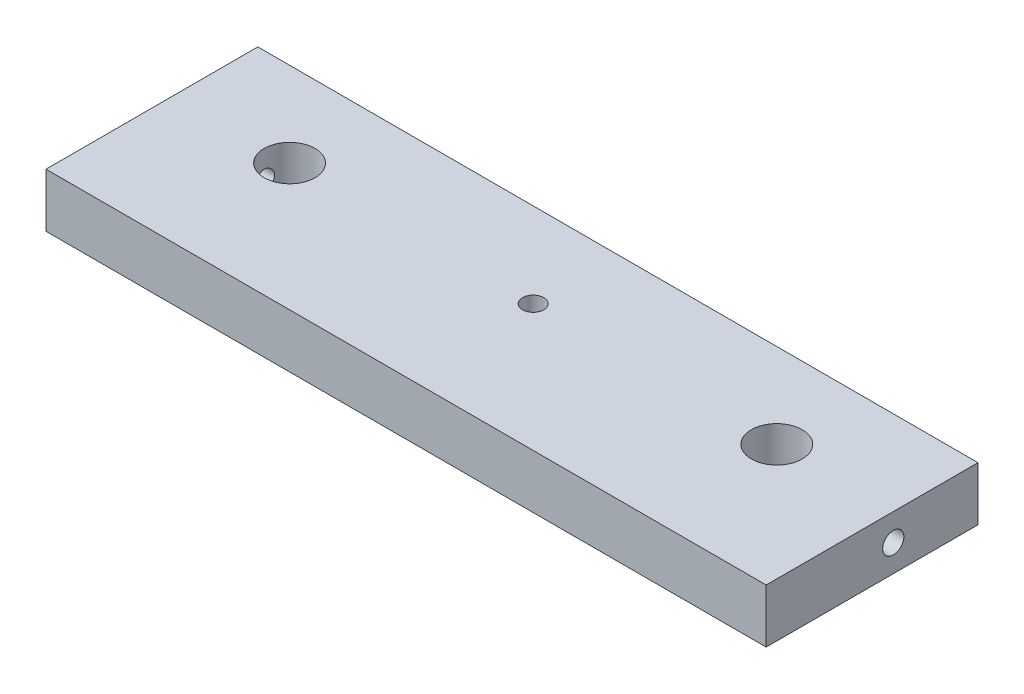
SolidWorks part; units mm, degrees
material "Liga 1060"
ref_plane "Frontal" through (0, 0, 0) normal (0, 0, 1) x (1, 0, 0)
ref_plane "Superior" through (0, 0, 0) normal (0, 1, 0) x (1, 0, 0)
ref_plane "Direito" through (0, 0, 0) normal (1, 0, 0) x (0, 0, -1)
sketch "Esboço1" plane through (0, 0, 0) normal (0, 1, 0) x (1, 0, 0)
  line L1 (-75, 20) -> (75, 20)
  line L2 (-75, 20) -> (-75, -20)
  line L3 (-75, -20) -> (75, -20)
  line L4 (75, 20) -> (75, -20)
  line L5 (-75, 20) -> (75, -20) construction
  line L6 (-75, -20) -> (75, 20) construction
  circle A0 centre (0, 0) radius 2.5
  circle A1 centre (-57.5, 0) radius 6
  circle A2 centre (57.5, 0) radius 6
  point P0 (0, 0)
  dimension "D3" = 5
  dimension "D4" = 12
  dimension "D5" = 12
  dimension "D1" = 150
  dimension "D2" = 40
  dimension "D6" = 17.5
  dimension "D7" = 17.5
  dimension "D8" = 20
extrude "Ressalto-extrusão1" add sketch "Esboço1" along normal blind 12.7
sketch "Esboço4" plane through (0, 0, 0) normal (0, -1, 0) x (1, 0, 0)
  circle A0 centre (0, 0) radius 5.5
  dimension "D1" = 11
extrude "Corte-extrusão1" cut sketch "Esboço4" against normal blind 8
sketch "Esboço7" plane through (0, 0, 0) normal (0, -1, 0) x (1, 0, 0)
  line L0 (75, 20) -> (-75, 20)
  line L1 (75, 20) -> (75, 30)
  line L2 (-75, 20) -> (-75, 30)
  line L3 (75, 30) -> (-75, 30)
  dimension "D1" = 10
extrude "Ressalto-extrusão4" add sketch "Esboço7" against normal up to surface (12.7 mm away) up to face at (-57.5, 12.7, 6)
sketch "Esboço8" plane through (0, 0, 0) normal (0, -1, 0) x (1, 0, 0)
  line L0 (-75, -20) -> (-75, 30)
  line L1 (-75, -20) -> (-85, -20)
  line L2 (-75, 30) -> (-85, 30)
  line L3 (-85, -20) -> (-85, 30)
  line L4 (-75, -20) -> (-75, 30) construction
  line L5 (75, -20) -> (75, 30)
  line L6 (75, -20) -> (85, -20)
  line L7 (75, 30) -> (85, 30)
  line L8 (85, -20) -> (85, 30)
  dimension "D1" = 10
  dimension "D2" = 10
extrude "Ressalto-extrusão5" add sketch "Esboço8" against normal up to surface (12.7 mm away) up to face at (-57.5, 12.7, 6)
sketch "Esboço9" plane through (85, 0, 0) normal (1, 0, 0) x (0, 0, -1)
  line L0 (-30, 6.35) -> (20, 6.35) construction
  line L1 (-30, 12.7) -> (-30, 0) construction
  line L2 (20, 12.7) -> (20, 0) construction
  circle A0 centre (0, 6.35) radius 2
  point P8 (0, 0)
  dimension "D1" = 4
  dimension "D2" = 20
extrude "Corte-extrusão2" cut sketch "Esboço9" against normal blind 10
hole_wizard "Furo roscado de M52" positions "Esboço12" profile "Esboço13" tap size "M5" standard "ISO"
sketch "Esboço12" plane through (85, 0, 0) normal (1, 0, 0) x (0, 0, -1)
  point P0 (0, 6.35)
sketch "Esboço13" plane through (85, 6.35, 0) normal (0, 1, 0) x (0, 0, -1)
  line L0 (0, 0) -> (0, 30.2618)
  line L1 (0, 30.2618) -> (2.1, 29)
  line L2 (2.1, 29) -> (2.1, 5)
  line L3 (2.1, 5) -> (2.5, 5)
  line L4 (2.5, 5) -> (2.5, 0)
  line L5 (2.5, 0) -> (0, 0)
  line L10 (0, 30.2618) -> (-2.1, 29) construction
  line L11 (0, -6.35) -> (0, 107.95) construction
  dimension "Tap Drill Dia." = 4.2
  dimension "Tap Drill Depth" = 29
  dimension "Thread Major Dia." = 5
  dimension "Thread Depth" = 5
  dimension "Drill Angle" = 118
mirror "Espelhar1" about plane through (0, 0, 0) normal (1, 0, 0) of "Furo roscado de M52", "Corte-extrusão2"
